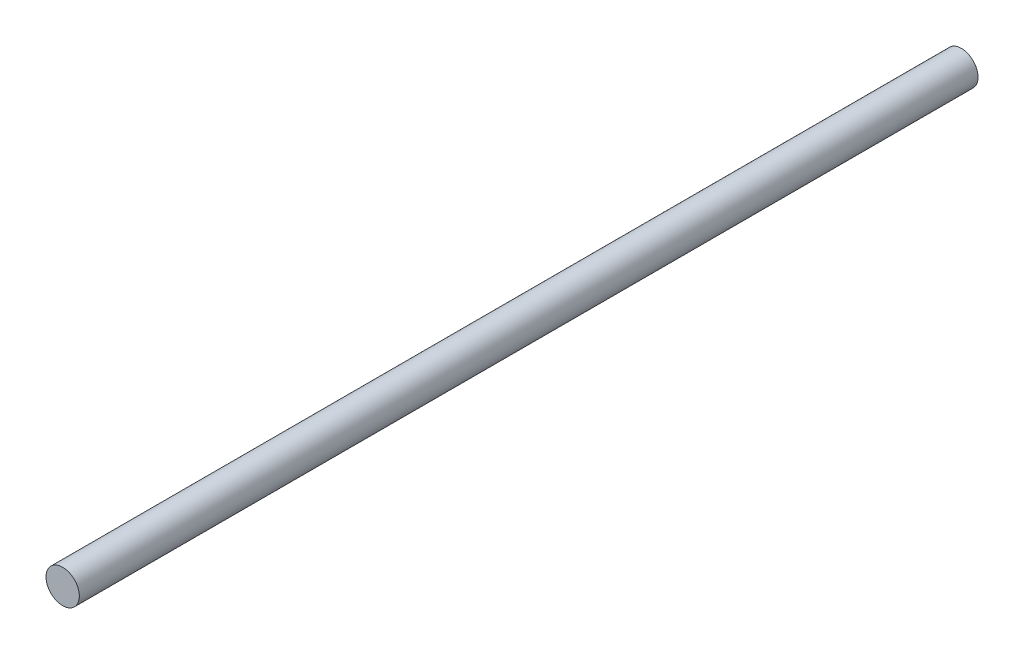
SolidWorks part; units mm, degrees
ref_plane "前视基准面" through (0, 0, 0) normal (0, 0, 1) x (1, 0, 0)
ref_plane "上视基准面" through (0, 0, 0) normal (0, 1, 0) x (1, 0, 0)
ref_plane "右视基准面" through (0, 0, 0) normal (1, 0, 0) x (0, 0, -1)
other "Configuration Table"
sketch "草图1" plane through (0, 0, 0) normal (0, 0, 1) x (1, 0, 0)
  circle A0 centre (0, 0) radius 3.8
  dimension "diameter" = 7.6
extrude "Cable" add sketch "草图1" along normal blind 205
